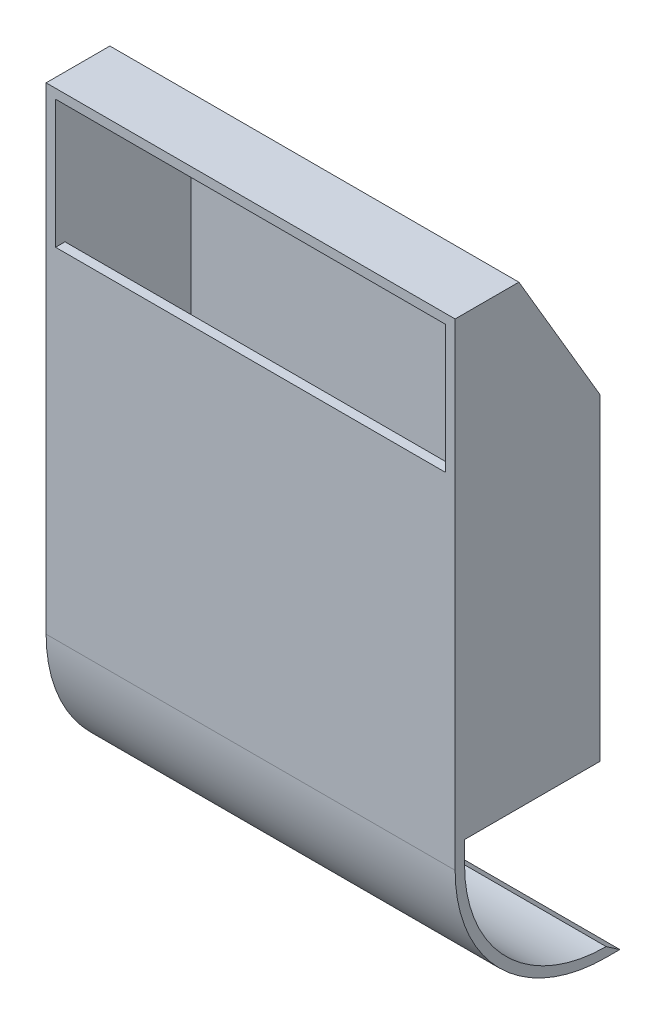
SolidWorks part; units mm, degrees
ref_plane "Front Plane" through (0, 0, 0) normal (0, 0, 1) x (1, 0, 0)
ref_plane "Top Plane" through (0, 0, 0) normal (0, 1, 0) x (1, 0, 0)
ref_plane "Right Plane" through (0, 0, 0) normal (1, 0, 0) x (0, 0, -1)
sketch "Sketch1" plane through (0, 0, 0) normal (1, 0, 0) x (0, 0, -1)
  line L0 (0, 0) -> (0, 108)
  line L1 (3, 0) -> (3, 108)
  line L2 (48, -45) -> (52.3715, -48)
  line L3 (52.3715, -48) -> (48, -48)
  line L4 (3, 108) -> (0, 108)
  arc A0 (0, 0) -> (48, -48) centre (48, 0) ccw
  arc A1 (3, 0) -> (48, -45) centre (48, 0) ccw
  dimension "D2" = 45
  dimension "D3" = 108
  dimension "D1" = 3
extrude "Boss-Extrude1" add sketch "Sketch1" along normal blind 130
sketch "Sketch2" plane through (0, 0, -3) normal (0, 0, -1) x (-1, 0, 0)
  line L1 (-130, 108) -> (-127, 108)
  line L2 (-130, 108) -> (-130, 6.9609)
  line L3 (-130, 6.9609) -> (-127, 6.9609)
  line L4 (-127, 108) -> (-127, 6.9609)
  line L5 (0, 0) -> (0, 108) construction
  line L6 (0, 108) -> (-3, 108)
  line L7 (0, 108) -> (0, 6.9609)
  line L8 (0, 6.9609) -> (-3, 6.9609)
  line L9 (-3, 108) -> (-3, 6.9609)
  line L10 (-130, 108) -> (0, 108) construction
  dimension "D1" = 3
  dimension "D2" = 3
extrude "Boss-Extrude2" add sketch "Sketch2" along normal blind 40
sketch "Sketch3" plane through (0, 0, -43) normal (0, 0, -1) x (-1, 0, 0)
  line L1 (-130, 108) -> (0, 108)
  line L2 (-130, 108) -> (-130, 6.9609)
  line L3 (-130, 6.9609) -> (0, 6.9609)
  line L4 (0, 108) -> (0, 6.9609)
extrude "Boss-Extrude3" add sketch "Sketch3" along normal blind 3
sketch "Sketch5" plane through (130, 0, 0) normal (1, 0, 0) x (0, 0, -1)
  line L0 (43.0407, 108) -> (19.5047, 148.7654)
  line L1 (46, 108) -> (0, 108) construction
  line L2 (19.5047, 148.7654) -> (0, 148.7654)
  line L3 (0, 148.7654) -> (0, 151.7654)
  line L4 (0, 151.7654) -> (20.2658, 151.7654)
  line L5 (20.2658, 151.7654) -> (46, 108)
  line L6 (0, 108) -> (0, 0) construction
  line L8 (46, 108) -> (43.0407, 108)
  dimension "D1" = 60
  dimension "D2" = 3
  dimension "D3" = 40.7654
extrude "Boss-Extrude4" add sketch "Sketch5" against normal blind 130
sketch "Sketch6" plane through (130, 0, 0) normal (1, 0, 0) x (0, 0, -1)
  line L0 (43.0407, 108) -> (0, 108) construction
  line L1 (19.5047, 148.7654) -> (43.0407, 108) construction
  line L2 (0, 148.7654) -> (19.5047, 148.7654) construction
  line L3 (43.0407, 108) -> (0, 108)
  line L4 (19.5047, 148.7654) -> (43.0407, 108)
  line L5 (0, 148.7654) -> (19.5047, 148.7654)
  line L6 (0, 148.7654) -> (0, 108)
extrude "Boss-Extrude5" add sketch "Sketch6" against normal blind 3
sketch "Sketch7" plane through (0, 0, 0) normal (-1, 0, 0) x (0, 0, 1)
  line L0 (-43.0407, 108) -> (0, 108) construction
  line L1 (-19.5047, 148.7654) -> (-43.0407, 108) construction
  line L2 (0, 148.7654) -> (-19.5047, 148.7654) construction
  line L3 (0, 148.7654) -> (0, 108) construction
  line L4 (-43.0407, 108) -> (0, 108)
  line L5 (-19.5047, 148.7654) -> (-43.0407, 108)
  line L6 (0, 148.7654) -> (-19.5047, 148.7654)
  line L7 (0, 148.7654) -> (0, 108)
extrude "Boss-Extrude6" add sketch "Sketch7" against normal blind 3
